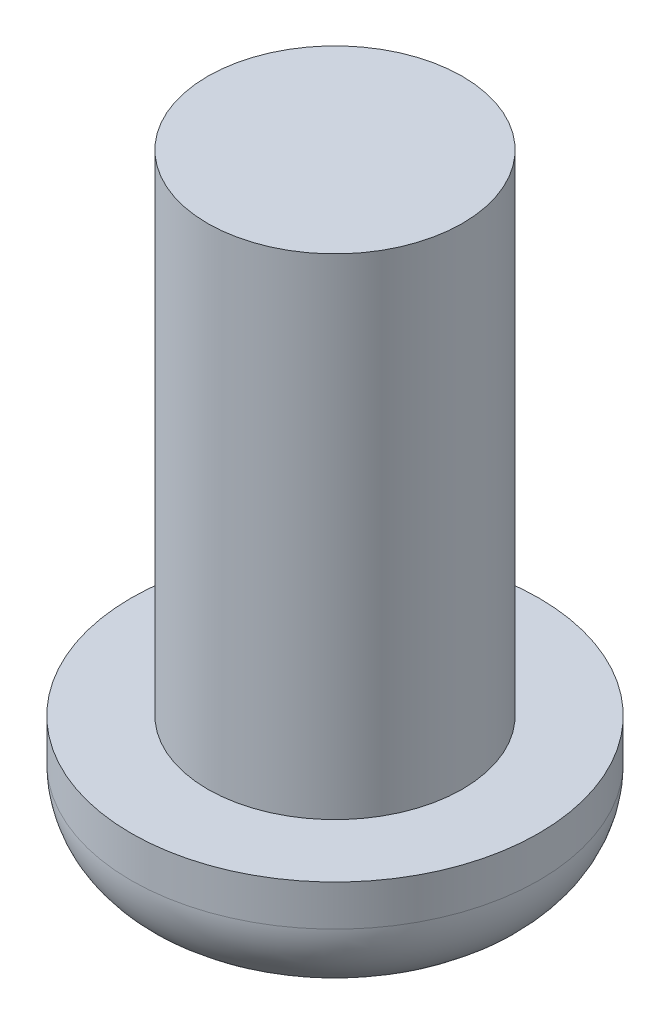
SolidWorks part; units mm, degrees
ref_plane "Front Plane" through (0, 0, 0) normal (0, 0, 1) x (1, 0, 0)
ref_plane "Top Plane" through (0, 0, 0) normal (0, 1, 0) x (1, 0, 0)
ref_plane "Right Plane" through (0, 0, 0) normal (1, 0, 0) x (0, 0, -1)
sketch "Sketch1" plane through (0, 0, 0) normal (0, 1, 0) x (1, 0, 0)
  circle A0 centre (0, 0) radius 2.4765
  dimension "D1" = 4.953
extrude "Boss-Extrude1" add sketch "Sketch1" along normal blind 9.525
sketch "Sketch2" plane through (0, 0, 0) normal (0, -1, 0) x (1, 0, 0)
  circle A0 centre (0, 0) radius 3.9624
  dimension "D1" = 7.9248
extrude "Boss-Extrude2" add sketch "Sketch2" along normal blind 2.3813
sketch "Sketch3" plane through (0, -2.3813, 0) normal (0, -1, 0) x (1, 0, 0)
  line L1 (2.0622, 0) -> (1.0311, 1.7859)
  line L2 (1.0311, 1.7859) -> (-1.0311, 1.7859)
  line L3 (-1.0311, 1.7859) -> (-2.0622, 0)
  line L4 (-2.0622, 0) -> (-1.0311, -1.7859)
  line L5 (-1.0311, -1.7859) -> (1.0311, -1.7859)
  line L6 (1.0311, -1.7859) -> (2.0622, 0)
  circle A0 centre (0, 0) radius 1.7859 construction
  dimension "D1" = 3.5719
extrude "Cut-Extrude1" cut sketch "Sketch3" against normal blind 2.286
fillet "Fillet1" radius 1.5875 1 edges at (0, -2.3813, -3.9624)
